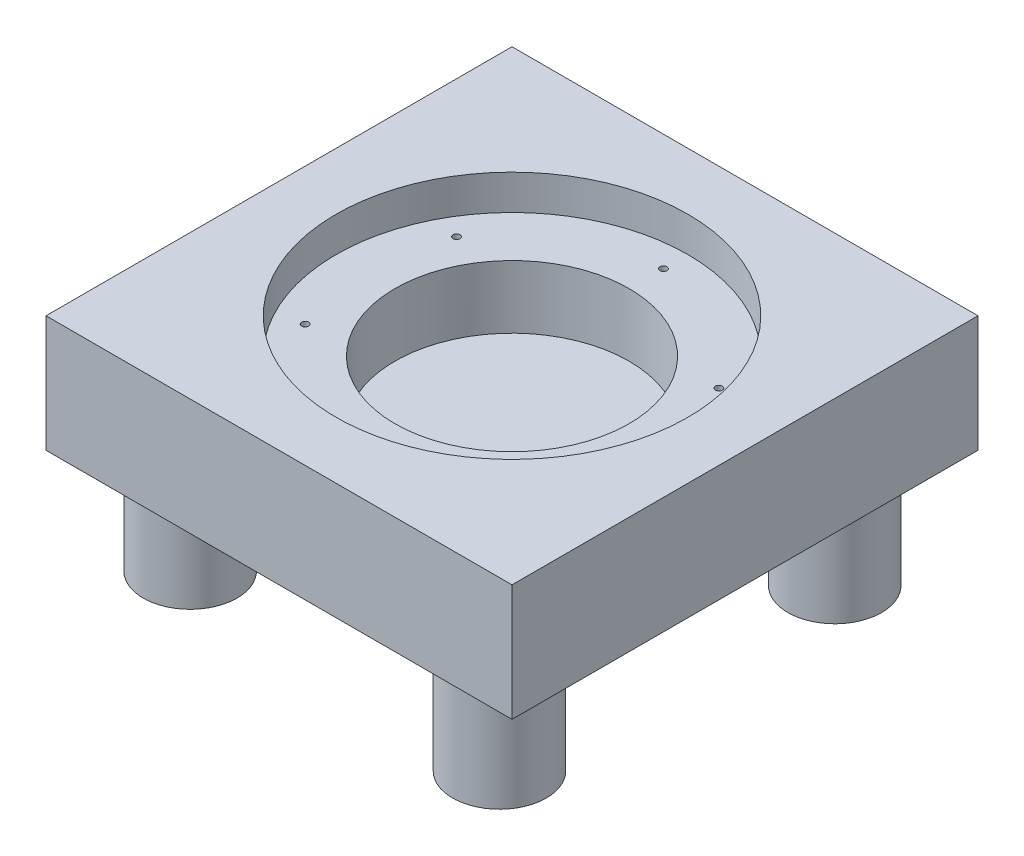
SolidWorks part; units mm, degrees
ref_plane "Front Plane" through (0, 0, 0) normal (0, 0, 1) x (1, 0, 0)
ref_plane "Top Plane" through (0, 0, 0) normal (0, 1, 0) x (1, 0, 0)
ref_plane "Right Plane" through (0, 0, 0) normal (1, 0, 0) x (0, 0, -1)
sketch "Sketch2" plane through (0, 0, 0) normal (0, 1, 0) x (1, 0, 0)
  line L1 (-100, -100) -> (100, -100)
  line L2 (-100, -100) -> (-100, 100)
  line L3 (-100, 100) -> (100, 100)
  line L4 (100, -100) -> (100, 100)
  line L5 (-100, -100) -> (100, 100) construction
  line L6 (-100, 100) -> (100, -100) construction
  point P0 (0, 0)
  dimension "D1" = 200
  dimension "D2" = 200
extrude "Boss-Extrude1" add sketch "Sketch2" along normal blind 50
sketch "Sketch5" plane through (0, 50, 0) normal (0, 1, 0) x (1, 0, 0)
  circle A0 centre (0, 0) radius 75.5
  dimension "D1" = 151
extrude "Cut-Extrude1" cut sketch "Sketch5" against normal blind 15 and the other way through all
sketch "Sketch7" plane through (0, 35, 0) normal (0, 1, 0) x (1, 0, 0)
  circle A0 centre (0, 0) radius 50.25
  dimension "D1" = 100.5
extrude "Cut-Extrude2" cut sketch "Sketch7" against normal through all both and the other way through all contours A0
sketch "Sketch12" plane through (0, 0, 0) normal (0, -1, 0) x (1, 0, 0)
  circle A0 centre (-74.1688, 63.9634) radius 20.1233
extrude "Boss-Extrude2" add sketch "Sketch12" along normal blind 50 contours A0
pattern_circular "CirPattern1" count 4 every 92 about axis through (0, 0, 0) along (0, 1, 0) of "Boss-Extrude2"
sketch "Sketch13" plane through (0, 35, 0) normal (0, 1, 0) x (1, 0, 0)
  circle A3 centre (0, 65) radius 1.5
  dimension "D2" = 3
extrude "Cut-Extrude3" cut sketch "Sketch13" against normal blind 10
pattern_circular "CirPattern2" count 6 over 360 about axis through (0, 0, 0) along (0, 1, 0) of "Cut-Extrude3"
sketch "Sketch14" plane through (0, 0, 0) normal (0, -1, 0) x (1, 0, 0)
  circle A0 centre (0, 0) radius 50.25
  circle A1 centre (0, 0) radius 50.25 construction
extrude "Boss-Extrude3" add sketch "Sketch14" against normal blind 8
